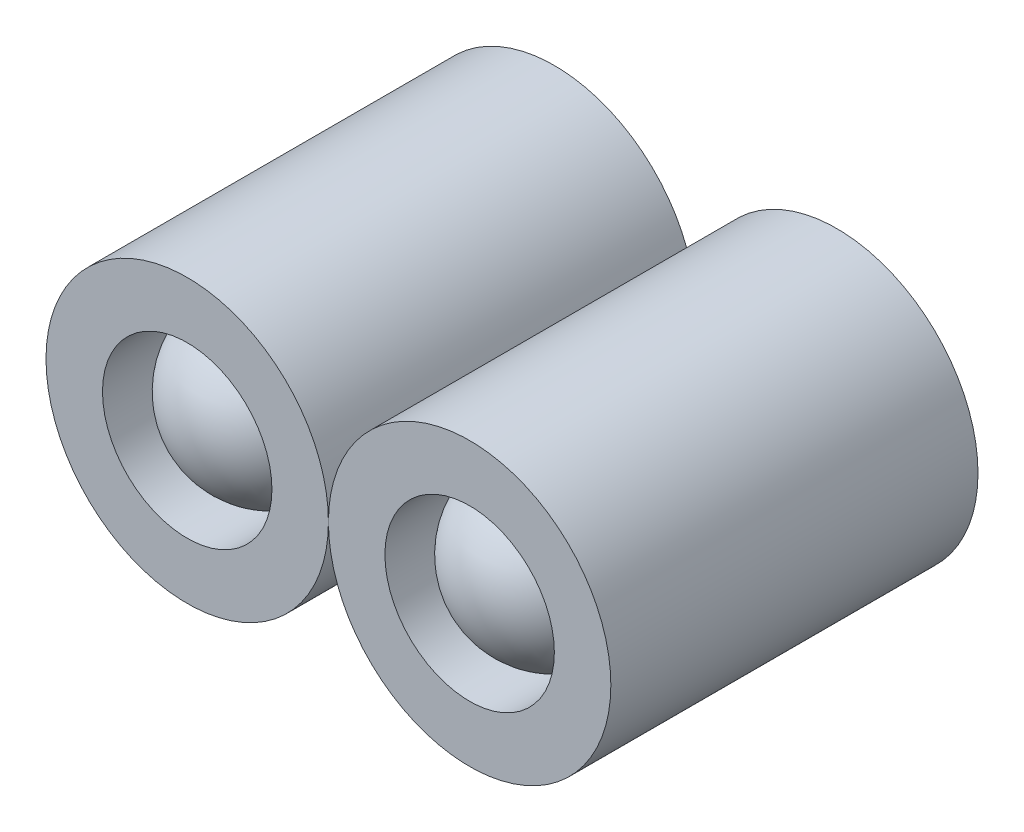
SolidWorks part; units mm, degrees
ref_plane "前视基准面" through (0, 0, 0) normal (0, 0, 1) x (1, 0, 0)
ref_plane "上视基准面" through (0, 0, 0) normal (0, 1, 0) x (1, 0, 0)
ref_plane "右视基准面" through (0, 0, 0) normal (1, 0, 0) x (0, 0, -1)
sketch "草图1" plane through (0, 0, 0) normal (0, 0, 1) x (1, 0, 0)
  circle A0 centre (-22.4336, 17.4497) radius 2.5
  circle A1 centre (-22.4336, 17.4497) radius 1.5
extrude "凸台-拉伸1" add sketch "草图1" along normal blind 6.5
sketch "草图2" plane through (0, 0, 0) normal (0, 0, 1) x (1, 0, 0)
  circle A0 centre (-17.4336, 17.4497) radius 2.5
  circle A1 centre (-22.4336, 17.4497) radius 2.5 construction
  circle A2 centre (-17.4336, 17.4497) radius 1.5
  dimension "D1" = 5
  dimension "D2" = 0
extrude "凸台-拉伸2" add sketch "草图2" along normal blind 6.5 separate body
sketch "草图3" plane through (0, 0, 0) normal (0, 0, 1) x (1, 0, 0)
  circle A0 centre (-22.4336, 17.4497) radius 1.5
  circle A1 centre (-17.4336, 17.4497) radius 1.5
extrude "凸台-拉伸3" add sketch "草图3" along normal blind 5
sketch "草图4" plane through (0, 0, 5) normal (0, 0, 1) x (1, 0, 0)
  line L0 (-22.4336, 18.9497) -> (-22.4336, 15.9497)
  arc A0 (-22.4336, 15.9497) -> (-22.4336, 18.9497) centre (-22.4336, 17.4497) ccw
revolve "旋转1" add sketch "草图4" angle 360 about L0
sketch "草图5" plane through (0, 0, 5) normal (0, 0, 1) x (1, 0, 0)
  line L0 (-17.4336, 18.9497) -> (-17.4336, 15.9497)
  arc A0 (-17.4336, 15.9497) -> (-17.4336, 18.9497) centre (-17.4336, 17.4497) ccw
revolve "旋转2" add sketch "草图5" angle 360 about L0
